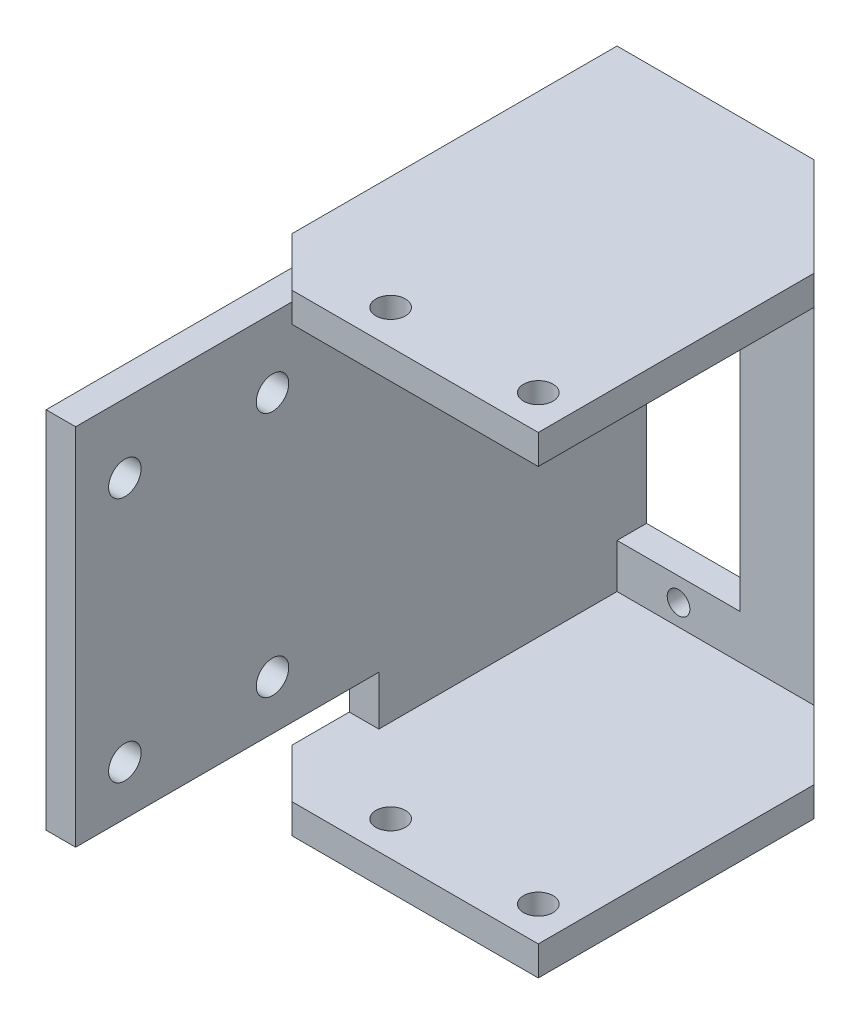
SolidWorks part; units mm, degrees
ref_plane "前视基准面" through (0, 0, 0) normal (0, 0, 1) x (1, 0, 0)
ref_plane "上视基准面" through (0, 0, 0) normal (0, 1, 0) x (1, 0, 0)
ref_plane "右视基准面" through (0, 0, 0) normal (1, 0, 0) x (0, 0, -1)
other "Configuration Table"
sketch "草图1" plane through (0, 0, 0) normal (0, 0, 1) x (1, 0, 0)
  line L1 (0, 0) -> (30, 0)
  line L2 (0, 0) -> (0, 48)
  line L3 (0, 48) -> (30, 48)
  line L4 (30, 0) -> (30, 48)
  dimension "D1" = 48
  dimension "D2" = 30
extrude "凸台-拉伸1" add sketch "草图1" along normal blind 3
sketch "草图3" plane through (0, 0, 3) normal (0, 0, 1) x (1, 0, 0)
  line L0 (30, 0) -> (30, 48) construction
  line L1 (0, 48) -> (30, 48)
  line L2 (0, 48) -> (0, 45)
  line L3 (0, 45) -> (30, 45)
  line L4 (30, 48) -> (30, 45)
  line L6 (0, 0) -> (30, 0)
  line L7 (0, 0) -> (0, 3)
  line L8 (0, 3) -> (30, 3)
  line L9 (30, 0) -> (30, 3)
  dimension "D1" = 3
  dimension "D2" = 3
extrude "凸台-拉伸2" add sketch "草图3" along normal blind 35
sketch "草图4" plane through (0, 0, 0) normal (0, 0, -1) x (-1, 0, 0)
  line L0 (0, 48) -> (0, 0) construction
  circle A1 centre (-9.25, 37.75) radius 2
  dimension "D1" = 4
  dimension "D2" = 9.25
sketch "草图5" plane through (0, 0, 0) normal (0, -1, 0) x (1, 0, 0)
  line L0 (0, 33) -> (5, 38)
  line L1 (0, 38) -> (0, 0) construction
  line L2 (0, 38) -> (30, 38) construction
  line L3 (5, 38) -> (0, 38)
  line L4 (0, 38) -> (0, 33)
  dimension "D1" = 45
  dimension "D2" = 5
extrude "切除-拉伸2" cut sketch "草图5" against normal through all
sketch "草图6" plane through (0, 0, 0) normal (0, -1, 0) x (1, 0, 0)
  line L0 (20, 0) -> (30, 10)
  line L1 (0, 0) -> (30, 0) construction
  line L2 (30, 38) -> (30, 0) construction
  line L3 (30, 10) -> (30, 0)
  line L4 (30, 0) -> (20, 0)
  dimension "D1" = 45
  dimension "D2" = 10
extrude "切除-拉伸3" cut sketch "草图6" against normal through all
sketch "草图7" plane through (0, 0, 3) normal (0, 0, 1) x (1, 0, 0)
  line L1 (0, 3) -> (3, 3)
  line L2 (0, 3) -> (0, 45)
  line L3 (0, 45) -> (3, 45)
  line L4 (3, 3) -> (3, 45)
  line L6 (5, 45) -> (0, 45) construction
extrude "凸台-拉伸3" add sketch "草图7" along normal blind 25
sketch "草图10" plane through (0, 0, 3) normal (0, 0, 1) x (1, 0, 0)
  line L0 (5, 45) -> (30, 45) construction
  line L1 (20.5, 12.8) -> (16.5, 12.8)
  line L2 (20.5, 12.8) -> (20.5, 45)
  line L3 (20.5, 45) -> (16.5, 45)
  line L4 (16.5, 12.8) -> (16.5, 45)
  dimension "D1" = 4
sketch "草图12" plane through (3, 0, 0) normal (1, 0, 0) x (0, 0, -1)
  line L1 (-23.1624, 31.4269) -> (-9.1105, 31.4269)
  line L2 (-23.1624, 31.4269) -> (-23.1624, 41.7502)
  line L3 (-23.1624, 41.7502) -> (-9.1105, 41.7502)
  line L4 (-9.1105, 31.4269) -> (-9.1105, 41.7502)
sketch "草图14" plane through (0, 0, 28) normal (0, 0, 1) x (1, 0, 0)
  line L4 (0, 45) -> (0, 3)
  line L5 (0, 3) -> (3, 3)
  line L6 (3, 3) -> (3, 45)
  line L7 (3, 45) -> (0, 45)
  line L8 (0, 45) -> (0, 3)
  line L10 (3, 3) -> (3, 45)
  line L11 (3, 45) -> (0, 45)
  line L12 (0, 3) -> (3, 3)
  dimension "D1" = 0
extrude "凸台-拉伸6" add sketch "草图14" along normal blind 30
sketch "草图15" plane through (0, 0, 0) normal (-1, 0, 0) x (0, 0, 1)
  circle A0 centre (38, 13) radius 1.65
  circle A1 centre (38, 38) radius 1.65
  circle A2 centre (53, 38) radius 1.65
  circle A3 centre (53, 13) radius 1.65
extrude "切除-拉伸6" cut sketch "草图15" against normal blind 4
sketch "草图16" plane through (0, 0, 3) normal (0, 0, 1) x (1, 0, 0)
  line L0 (3, 3) -> (3, 45) construction
  line L1 (15.5, 7.5) -> (3, 7.5)
  line L2 (15.5, 7.5) -> (15.5, 30.5)
  line L3 (15.5, 30.5) -> (3, 30.5)
  line L4 (3, 7.5) -> (3, 30.5)
  line L5 (3, 30.5) -> (15.5, 30.5) construction
  circle A0 centre (9.25, 32.85) radius 1.15
  circle A1 centre (9.25, 5.15) radius 1.15
  dimension "D1" = 2.3
  dimension "D2" = 2.3
extrude "切除-拉伸7" cut sketch "草图16" against normal blind 10
sketch "草图17" plane through (0, 0, 0) normal (-1, 0, 0) x (0, 0, 1)
  line L1 (58, 3) -> (27.2, 3)
  line L2 (58, 3) -> (58, 8)
  line L3 (58, 8) -> (27.2, 8)
  line L4 (27.2, 3) -> (27.2, 8)
extrude "切除-拉伸8" cut sketch "草图17" against normal blind 10
sketch "草图18" plane through (0, 48, 0) normal (0, 1, 0) x (1, 0, 0)
  line L0 (0, 0) -> (0, 9)
  line L1 (0, 9) -> (20, 9)
  line L2 (20, 9) -> (20, 0)
  line L3 (20, 0) -> (17, 0)
  line L4 (20, 0) -> (0, 0) construction
  line L5 (17, 0) -> (17, 6)
  line L6 (17, 6) -> (3, 6)
  line L7 (3, 6) -> (3, 0)
  line L8 (3, 0) -> (0, 0)
  dimension "D1" = 3
  dimension "D2" = 3
  dimension "D3" = 9
  dimension "D4" = 3
sketch "草图19" plane through (0, 0, 0) normal (0, 0, -1) x (-1, 0, 0)
sketch "草图20" plane through (0, 0, 0) normal (0, -1, 0) x (1, 0, 0)
  line L0 (0, 33) -> (0, 0) construction
  circle A1 centre (26.5, 34.5) radius 1.5
  circle A3 centre (11.5, 34.5) radius 1.5
  dimension "D1" = 3
  dimension "D2" = 3
  dimension "D3" = 11.5
  dimension "D4" = 15
extrude "切除-拉伸11" cut sketch "草图20" against normal through all
sketch "草图22" plane through (0, 0, 0) normal (0, 0, -1) x (-1, 0, 0)
  line L0 (-9.25, 5.15) -> (-9.25, 53.4853) construction
  circle A0 centre (-9.25, 37.75) radius 2
  circle A1 centre (-9.25, 13.75) radius 2 construction
  dimension "D1" = 24
  dimension "D2" = 4
extrude "切除-拉伸12" cut sketch "草图22" against normal up to next
sketch "草图23" plane through (0, 0, 3) normal (0, 0, 1) x (1, 0, 0)
  line L1 (6.3738, 35.5569) -> (11.9282, 35.5569)
  line L2 (6.3738, 35.5569) -> (6.3738, 40.2313)
  line L3 (6.3738, 40.2313) -> (11.9282, 40.2313)
  line L4 (11.9282, 35.5569) -> (11.9282, 40.2313)
  circle A0 centre (9.25, 37.75) radius 2 construction
  circle A1 centre (9.25, 37.75) radius 2
extrude "凸台-拉伸9" add sketch "草图23" along normal blind 3
sketch "草图25" plane through (0, 0, 3) normal (0, 0, 1) x (1, 0, 0)
  line L0 (9.25, 37.75) -> (9.25, 25.75) construction
  dimension "D1" = 12
